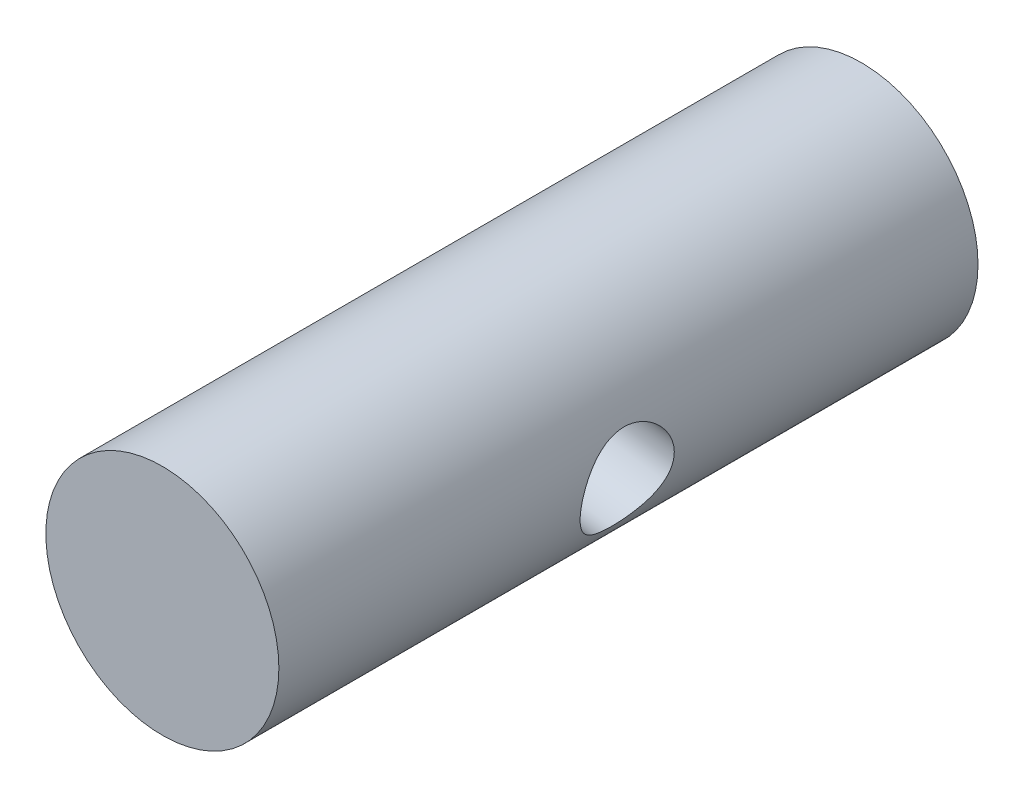
SolidWorks part; units mm, degrees
ref_plane "Front Plane" through (0, 0, 0) normal (0, 0, 1) x (1, 0, 0)
ref_plane "Top Plane" through (0, 0, 0) normal (0, 1, 0) x (1, 0, 0)
ref_plane "Right Plane" through (0, 0, 0) normal (1, 0, 0) x (0, 0, -1)
sketch "Sketch1" plane through (0, 0, 0) normal (0, 0, 1) x (1, 0, 0)
  circle A0 centre (-33.5766, 12.4461) radius 7.5
extrude "Boss-Extrude1" add sketch "Sketch1" along normal blind 45
sketch "Sketch2" plane through (0, 0, 45) normal (0, 0, 1) x (1, 0, 0)
  line L0 (-32.5731, 19.8787) -> (-34.5802, 5.0135) construction
  circle A0 centre (-33.5766, 12.4461) radius 7.5 construction
ref_plane "Plane1" through (-34.6259, 4.6752, 0) normal (-0.991, 0.1338, 0) x (-0.1338, -0.991, 0)
sketch "Sketch3" plane through (-34.6259, 4.6752, 0) normal (-0.991, 0.1338, 0) x (-0.1338, -0.991, 0)
  line L0 (-15.3414, 45) -> (-0.3414, 45) construction
  line L1 (-15.3414, 45) -> (-15.3414, 0) construction
  circle A0 centre (-7.8414, 22.5) radius 3
  dimension "D1" = 6
  dimension "D2" = 22.5
  dimension "D3" = 7.5
extrude "Cut-Extrude1" cut sketch "Sketch3" against normal through all both and the other way through all
